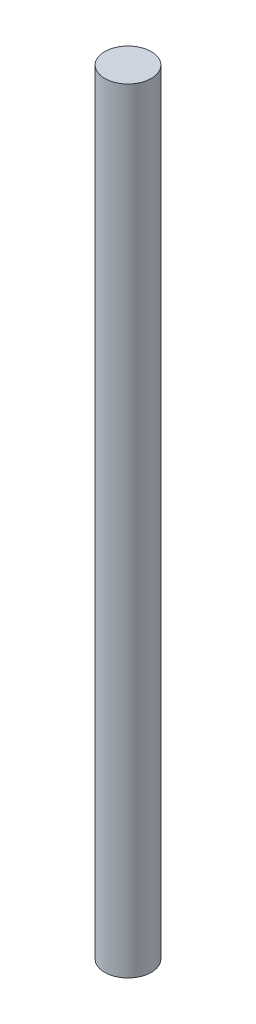
SolidWorks part; units mm, degrees
ref_plane "前视基准面" through (0, 0, 0) normal (0, 0, 1) x (1, 0, 0)
ref_plane "上视基准面" through (0, 0, 0) normal (0, 1, 0) x (1, 0, 0)
ref_plane "右视基准面" through (0, 0, 0) normal (1, 0, 0) x (0, 0, -1)
other "Configuration Table"
sketch "草图1" plane through (0, 0, 0) normal (0, 1, 0) x (1, 0, 0)
  circle A0 centre (0, 0) radius 35
  dimension "D1" = 70
extrude "凸台-拉伸1" add sketch "草图1" along normal blind 1164
